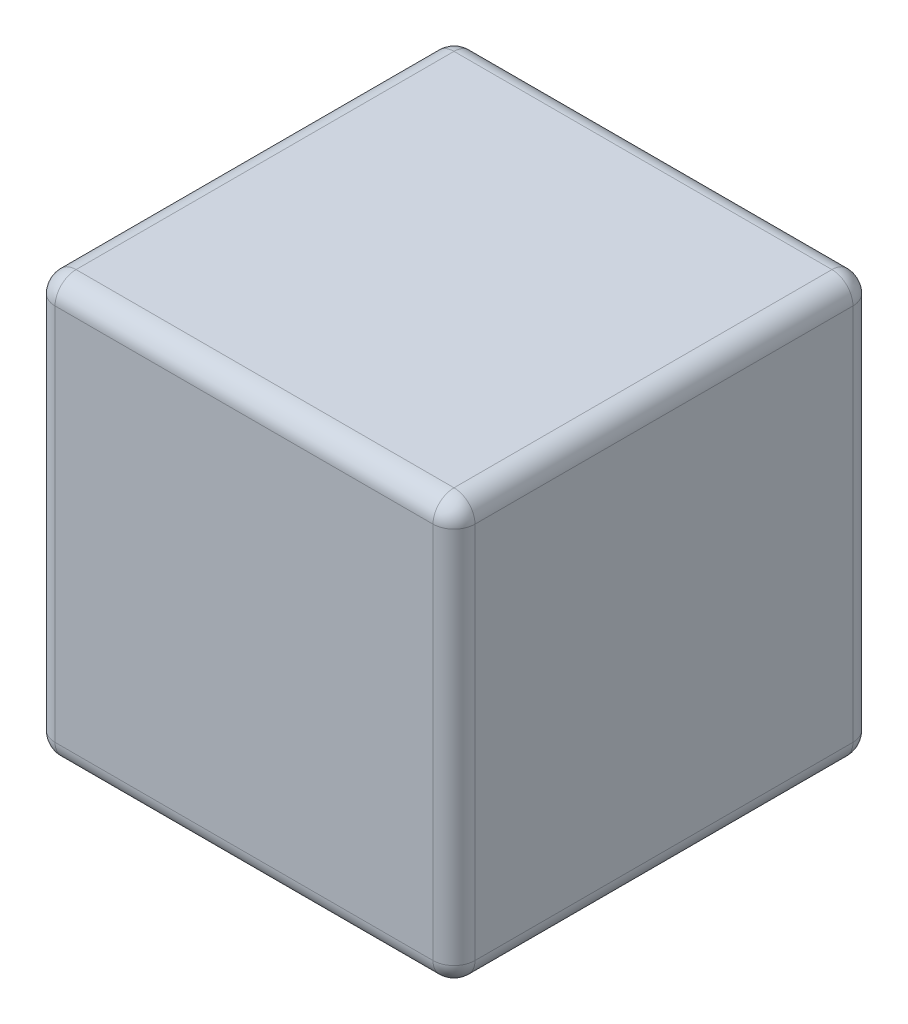
SolidWorks part; units mm, degrees
material "Titanium Ti-13V-11Cr-3Al Solution Treated"
ref_plane "Front Plane" through (0, 0, 0) normal (0, 0, 1) x (1, 0, 0)
ref_plane "Top Plane" through (0, 0, 0) normal (0, 1, 0) x (1, 0, 0)
ref_plane "Right Plane" through (0, 0, 0) normal (1, 0, 0) x (0, 0, -1)
sketch "Sketch1" plane through (0, 0, 0) normal (0, 1, 0) x (1, 0, 0)
  line L1 (0, 0) -> (100, 0)
  line L2 (0, 0) -> (0, 100)
  line L3 (0, 100) -> (100, 100)
  line L4 (100, 0) -> (100, 100)
  dimension "D1" = 100
  dimension "D2" = 100
extrude "Boss-Extrude1" add sketch "Sketch1" along normal blind 100
sketch "Sketch3" plane through (0, 0, -100) normal (0, 0, -1) x (-1, 0, 0)
  line L0 (-100, 100) -> (-100, 0) construction
  line L1 (-100, 100) -> (0, 100) construction
  circle A0 centre (-50, 50) radius 10
  point P6 (0, 0)
  point P7 (0, 0)
  dimension "D1" = 20
  dimension "D2" = 50
  dimension "D3" = 50
extrude "Cut-Extrude1" cut sketch "Sketch3" against normal blind 10
sketch "Sketch4" plane through (0, 0, 0) normal (0, -1, 0) x (1, 0, 0)
  line L0 (0, 0) -> (100, -100) construction
  line L1 (100, -100) -> (0, -100) construction
  line L2 (100, 0) -> (100, -100) construction
  line L3 (0, -100) -> (100, 0) construction
  circle A0 centre (21.7157, -78.2843) radius 10
  circle A1 centre (21.7157, -21.7157) radius 10
  circle A2 centre (78.2843, -78.2843) radius 10
  circle A3 centre (78.2843, -21.7157) radius 10
  circle A4 centre (50, -50) radius 10
  point P13 (0, 0)
  point P14 (28.7914, -63.3181)
  point P15 (0, 0)
  point P16 (20.936, -79.064)
  point P19 (20.936, -20.936)
  point P22 (79.064, -79.064)
  point P25 (79.064, -20.936)
  point P28 (50, -50)
  point P29 (0, 0)
  point P30 (0, 0)
  point P31 (17.9036, -17.9036)
  point P32 (20.936, -20.936)
  dimension "D1" = 20
  dimension "D2" = 40
  dimension "D3" = 40
  dimension "D4" = 40
  dimension "D5" = 40
extrude "Cut-Extrude2" cut sketch "Sketch4" against normal blind 10
fillet "Fillet5" radius 5 12 edges at (100, 50, -100) (100, 0, -50) (50, 100, -100) (100, 100, -50) (0, 50, -100) (0, 100, -50) (0, 0, -50) (0, 50, 0) (50, 100, 0) (100, 50, 0) (50, 0, 0) (50, 0, -100)
